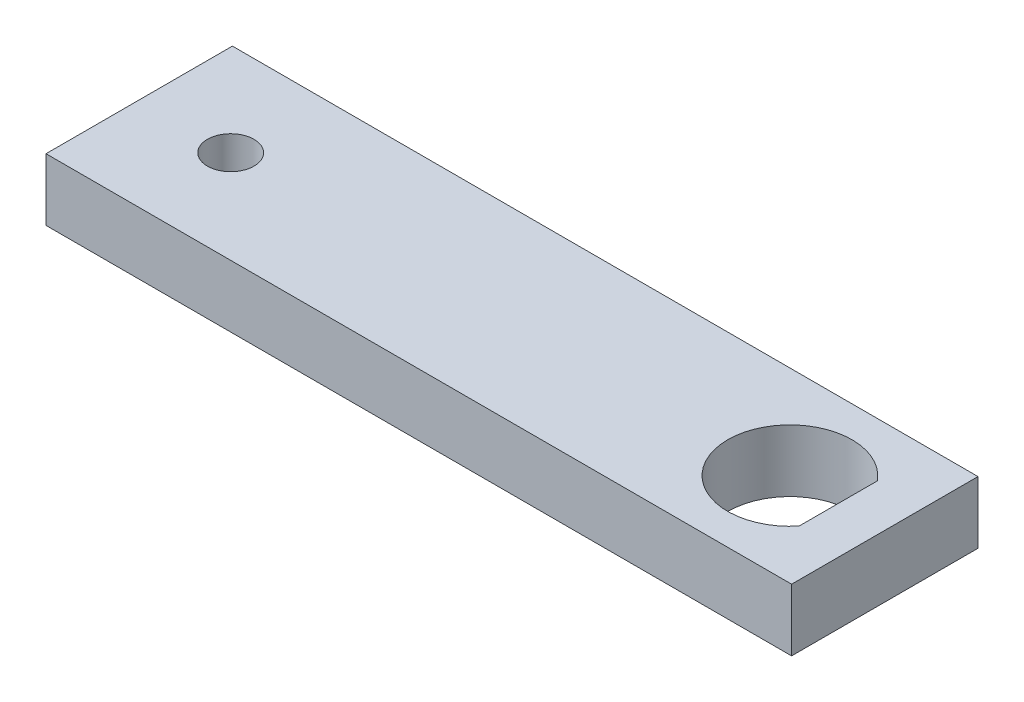
SolidWorks part; units mm, degrees
ref_plane "Front Plane" through (0, 0, 0) normal (0, 0, 1) x (1, 0, 0)
ref_plane "Top Plane" through (0, 0, 0) normal (0, 1, 0) x (1, 0, 0)
ref_plane "Right Plane" through (0, 0, 0) normal (1, 0, 0) x (0, 0, -1)
sketch "Sketch1" plane through (0, 0, 0) normal (0, 1, 0) x (1, 0, 0)
  line L1 (-38.1, -9.525) -> (38.1, -9.525)
  line L2 (-38.1, -9.525) -> (-38.1, 9.525)
  line L3 (-38.1, 9.525) -> (38.1, 9.525)
  line L4 (38.1, -9.525) -> (38.1, 9.525)
  line L5 (-38.1, -9.525) -> (38.1, 9.525) construction
  line L6 (-38.1, 9.525) -> (38.1, -9.525) construction
  line L7 (33.34, 3.9898) -> (33.34, -3.9898)
  arc A1 (33.34, 3.9898) -> (33.34, -3.9898) centre (28.4, 0) ccw
  circle A2 centre (-28.75, 0) radius 2.38
  point P0 (0, 0)
  point P8 (0, 0)
  dimension "D3" = 12.7
  dimension "D4" = 9.7
  dimension "D6" = 4.76
  dimension "D7" = 9.35
  dimension "D1" = 19.05
  dimension "D2" = 76.2
  dimension "D5" = 4.76
extrude "Boss-Extrude1" add sketch "Sketch1" along normal mid plane 6.35
